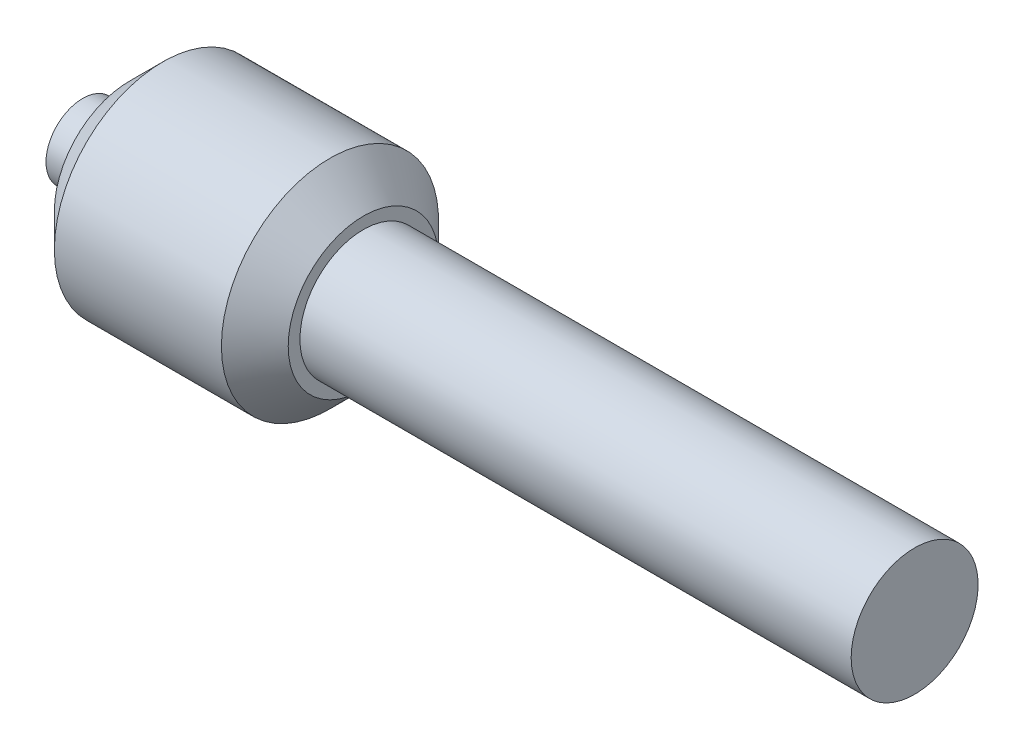
SolidWorks part; units mm, degrees
ref_plane "Front Plane" through (0, 0, 0) normal (0, 0, 1) x (1, 0, 0)
ref_plane "Top Plane" through (0, 0, 0) normal (0, 1, 0) x (1, 0, 0)
ref_plane "Right Plane" through (0, 0, 0) normal (1, 0, 0) x (0, 0, -1)
sketch "Sketch1" plane through (0, 0, 0) normal (0, 0, 1) x (1, 0, 0)
  line L0 (0, 0) -> (249, 0) construction
  line L1 (0, 11) -> (14, 11)
  line L2 (14, 22.5) -> (24, 32.5)
  line L3 (24, 32.5) -> (74, 32.5)
  line L4 (74, 32.5) -> (84, 22.5)
  line L5 (84, 22.5) -> (84, 19)
  line L6 (0, 11) -> (0, 0)
  line L7 (249, 19) -> (249, 0)
  line L8 (14, 11) -> (14, 22.5)
  line L9 (84, 19) -> (249, 19)
  line L10 (0, 0) -> (249, 0)
  dimension "D1" = 10
  dimension "D2" = 10
  dimension "D3" = 50
  dimension "D4" = 165
  dimension "D5" = 14
  dimension "D6" = 11
  dimension "D7" = 32.5
  dimension "D8" = 22.5
  dimension "D9" = 19
revolve "Revolve1" add sketch "Sketch1" angle 360 about L0
sketch "Sketch5" plane through (0, 0, 0) normal (-1, 0, 0) x (0, 0, 1)
  circle A1 centre (0, 0) radius 11
  circle A2 centre (0, 0) radius 11
  dimension "D1" = 0
hole_wizard "M12x1.5 Tapped Hole1" positions "3DSketch6" profile "Sketch7" tap size "M12x1.5" standard "ISO"
sketch3d "3DSketch6"
  point P5 (0, 0, 0)
  point P8 (0, 0, 0)
  point P11 (0, 0, 0)
sketch "Sketch7" plane through (0, 0, 0) normal (0, 1, 0) x (0, 0, 1)
  line L0 (0, 0) -> (0, 28)
  line L1 (0, 28) -> (5.25, 24.8455)
  line L2 (5.25, 24.8455) -> (5.25, 0.775)
  line L3 (5.25, 0.775) -> (6.025, 0)
  line L5 (6.025, 0) -> (0, 0)
  line L6 (-5.25, 0.775) -> (-6.025, 0) construction
  line L10 (0, 28) -> (-5.25, 24.8455) construction
  line L11 (0, -6.35) -> (0, 107.95) construction
  dimension "Tap Drill Dia." = 10.5
  dimension "Tap Drill Depth" = 28
  dimension "Near C'Sink Dia." = 12.05
  dimension "Near C'Sink Angle" = 90
  dimension "Drill Angle" = 118
cosmetic thread "Hole Thread1"
cosmetic thread "Hole Thread2"
